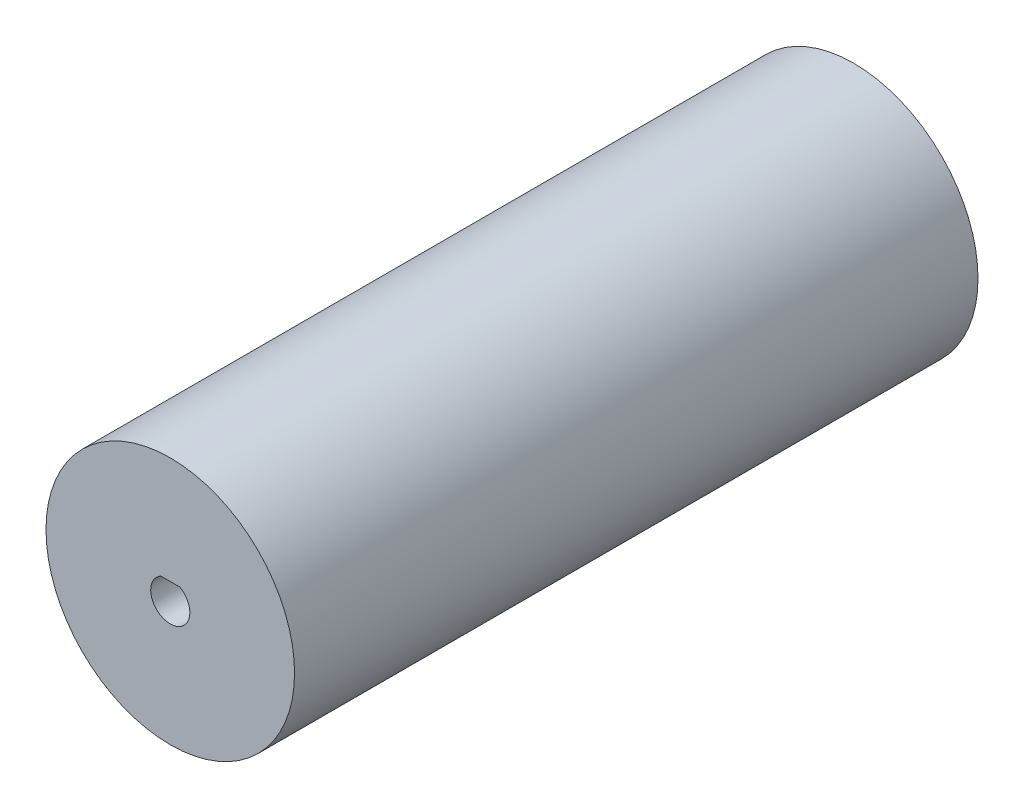
SolidWorks part; units mm, degrees
ref_plane "Front Plane" through (0, 0, 0) normal (0, 0, 1) x (1, 0, 0)
ref_plane "Top Plane" through (0, 0, 0) normal (0, 1, 0) x (1, 0, 0)
ref_plane "Right Plane" through (0, 0, 0) normal (1, 0, 0) x (0, 0, -1)
sketch "Sketch1" plane through (0, 0, 0) normal (0, 0, 1) x (1, 0, 0)
  circle A0 centre (0, 0) radius 12.7
  dimension "D1" = 25.4
extrude "Boss-Extrude1" add sketch "Sketch1" along normal blind 69.85 contours A0
sketch "Sketch2" plane through (0, 0, 69.85) normal (0, 0, 1) x (1, 0, 0)
  line L0 (0, 12.7) -> (0, -12.7) construction
  line L1 (-0.9682, 1.75) -> (0.9682, 1.75)
  circle A0 centre (0, 0) radius 12.7 construction
  arc A1 (-0.9682, 1.75) -> (0.9682, 1.75) centre (0, 0) ccw
  point P8 (0, 1.75)
  dimension "D1" = 2
  dimension "D2" = 1.75
extrude "Cut-Extrude1" cut sketch "Sketch2" against normal blind 10
sketch "Sketch3" plane through (0, 0, 0) normal (0, 0, -1) x (-1, 0, 0)
  circle A0 centre (0, 0) radius 3
  dimension "D1" = 6
extrude "Cut-Extrude2" cut sketch "Sketch3" against normal blind 34.925
